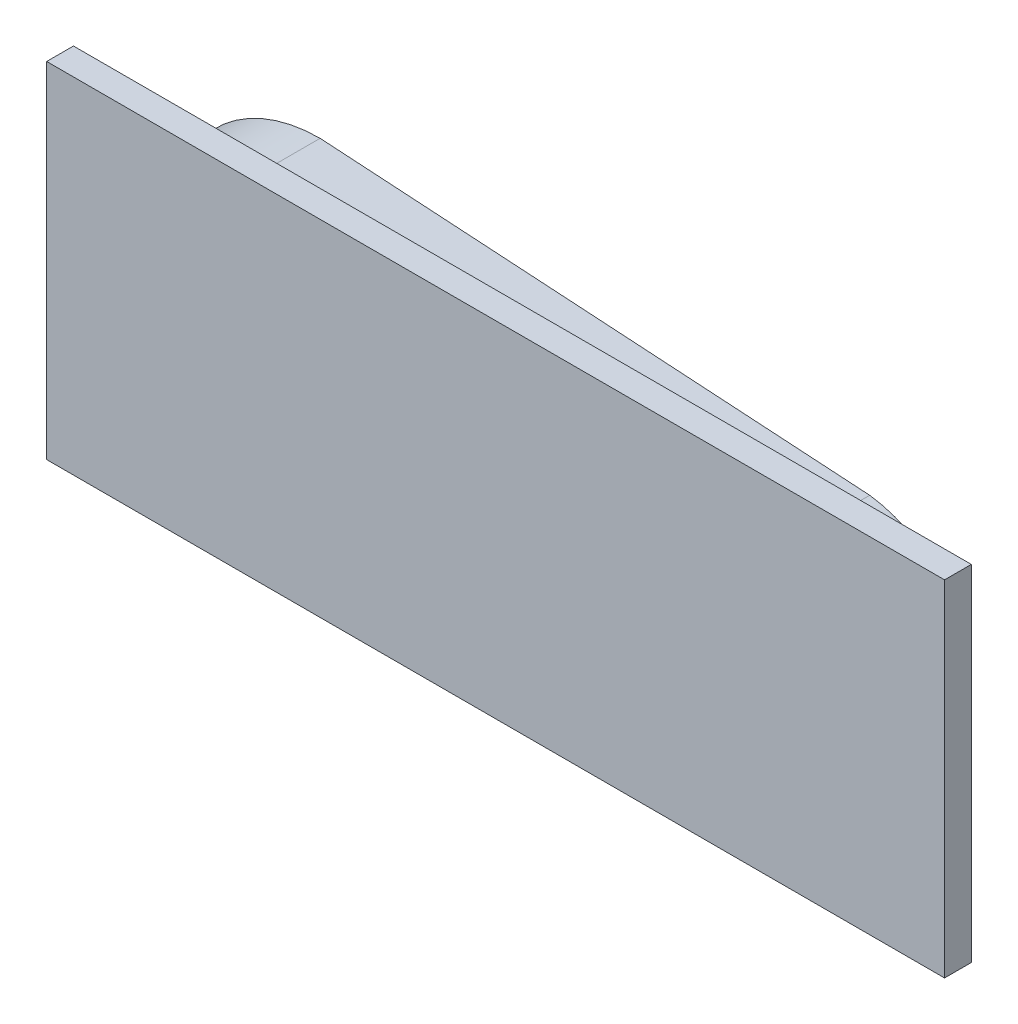
SolidWorks part; units mm, degrees
ref_plane "Front Plane" through (0, 0, 0) normal (0, 0, 1) x (1, 0, 0)
ref_plane "Top Plane" through (0, 0, 0) normal (0, 1, 0) x (1, 0, 0)
ref_plane "Right Plane" through (0, 0, 0) normal (1, 0, 0) x (0, 0, -1)
other "Configuration Table"
sketch "Sketch1" plane through (0, 0, 0) normal (0, 0, 1) x (-1, 0, 0)
  line L0 (4.8805, 3.4931) -> (-14.9, 2.25)
  line L5 (4.8805, -3.4931) -> (-14.9, -2.25)
  line L6 (-15.1634, 4.2418) -> (5.1, 5.5)
  line L7 (-15.2255, 2.2263) -> (-15.4241, -4.2176) construction
  line L8 (5.1, 3.5) -> (5.1, -3.5) construction
  line L9 (-15.4241, -4.2176) -> (5.1, -5.5)
  arc A0 (4.4153, -5.4572) -> (4.4196, 5.4578) centre (5.1, 0) ccw
  arc A3 (4.8805, -3.4931) -> (4.8805, 3.4931) centre (5.1, 0) ccw
  arc A4 (-14.9, 2.25) -> (-14.9, -2.25) centre (-14.9, 0) ccw
  arc A5 (-15.1634, 4.2418) -> (-14.905, -4.25) centre (-14.9, 0) ccw
extrude "Boss-Extrude1" add sketch "Sketch1" along normal blind 2 contours L6 A5 L9 A0 A4 L0 A3 L5
sketch "Sketch2" plane through (0, 0, 2) normal (0, 0, 1) x (1, 0, 0)
  line L1 (-12.3116, 5.8798) -> (21.219, 5.8798)
  line L2 (-12.3116, 5.8798) -> (-12.3116, -6.997)
  line L3 (-12.3116, -6.997) -> (21.219, -6.997)
  line L4 (21.219, 5.8798) -> (21.219, -6.997)
extrude "Boss-Extrude2" add sketch "Sketch2" along normal blind 1
